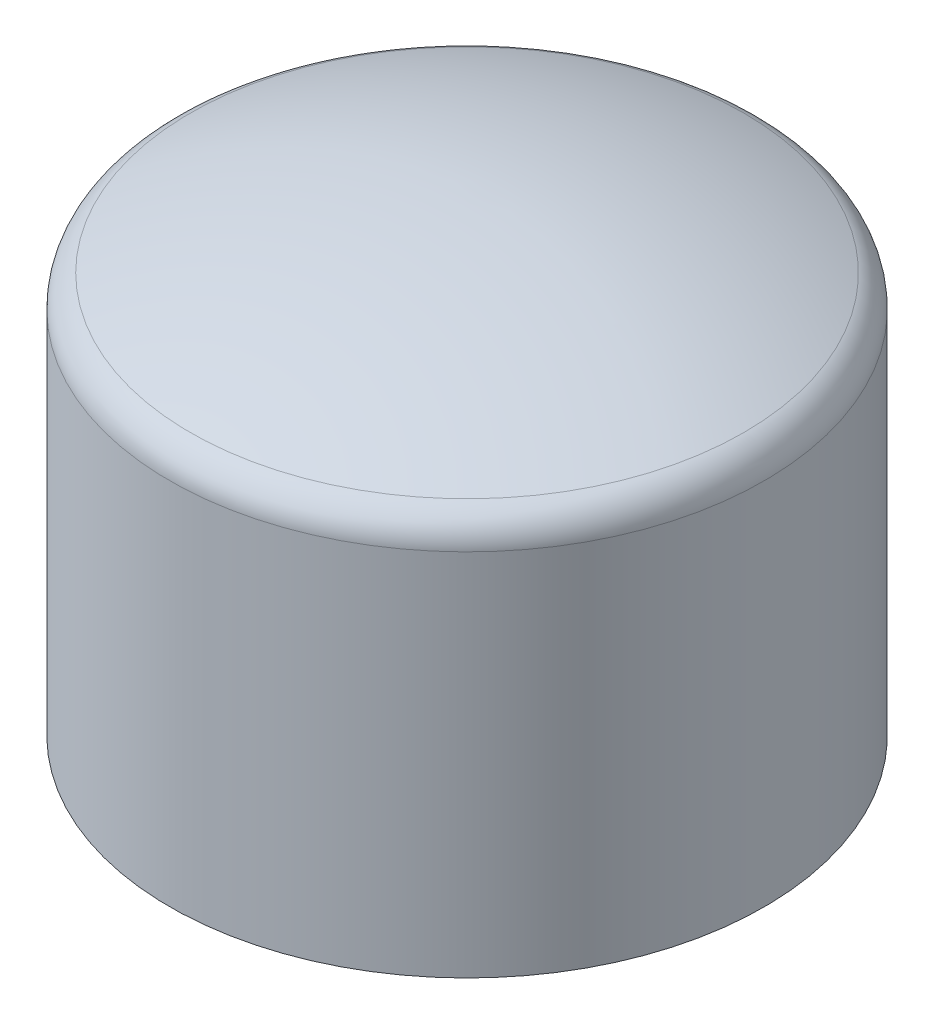
SolidWorks part; units mm, degrees
material "PVC 0.007 Plasticized"
ref_plane "Front Plane" through (0, 0, 0) normal (0, 0, 1) x (1, 0, 0)
ref_plane "Top Plane" through (0, 0, 0) normal (0, 1, 0) x (1, 0, 0)
ref_plane "Right Plane" through (0, 0, 0) normal (1, 0, 0) x (0, 0, -1)
sketch "Sketch1" plane through (0, 0, 0) normal (0, 0, 1) x (1, 0, 0)
  line L0 (0, 0) -> (0, 42.1284) construction
  line L1 (16.7005, 0) -> (21.844, 0)
  line L2 (21.844, 0) -> (21.844, 28.7382)
  line L3 (16.7005, 0) -> (16.7005, 25.4)
  line L4 (0, 33.782) -> (0, 28.6385)
  arc A0 (21.844, 28.7382) -> (0, 33.782) centre (0, -16.0418) ccw
  arc A1 (16.7005, 25.4) -> (0, 28.6385) centre (0, -16.0418) ccw
  dimension "D1" = 33.401
  dimension "D2" = 43.688
  dimension "D3" = 33.782
  dimension "D4" = 5.1435
  dimension "D5" = 25.4
revolve "Revolve1" add sketch "Sketch1" angle 360 about L0
fillet "Fillet1" radius 2.54 2 edges at (0, 25.4, -16.7005) (0, 28.7382, -21.844)
equation "\"D4@Sketch1\"=(\"D2@Sketch1\"-\"D1@Sketch1\")/2"
